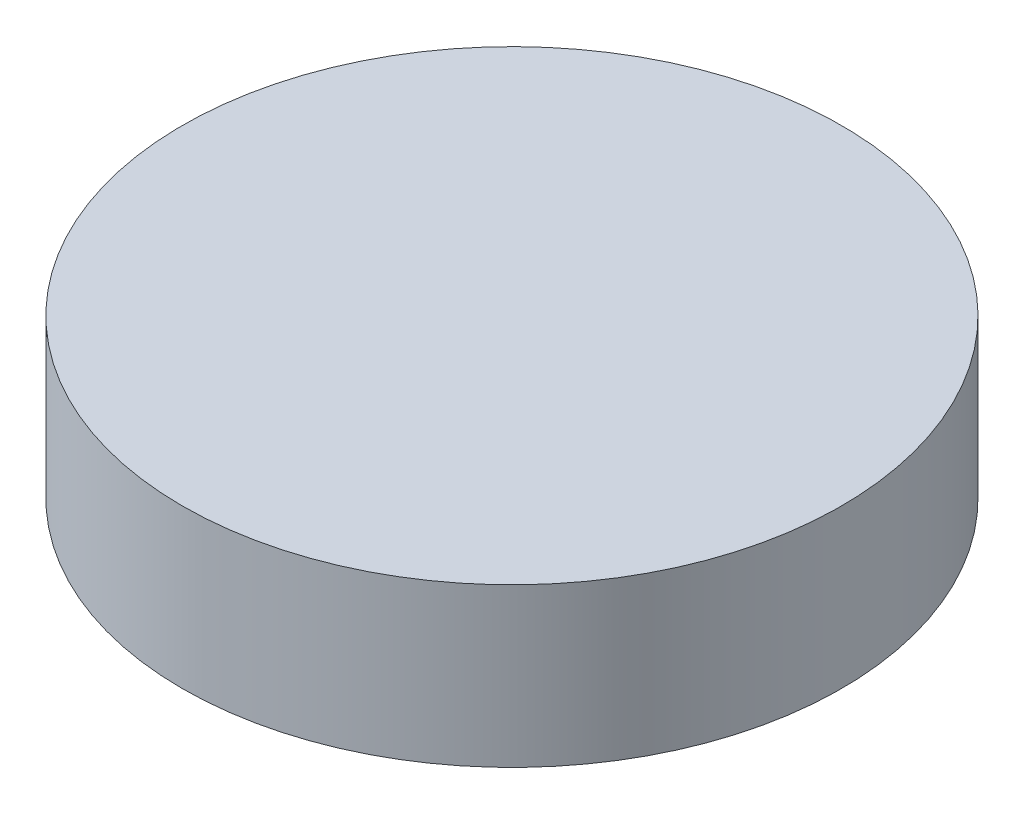
SolidWorks part; units mm, degrees
ref_plane "Front Plane" through (0, 0, 0) normal (0, 0, 1) x (1, 0, 0)
ref_plane "Top Plane" through (0, 0, 0) normal (0, 1, 0) x (1, 0, 0)
ref_plane "Right Plane" through (0, 0, 0) normal (1, 0, 0) x (0, 0, -1)
other "Configuration Table"
sketch "Sketch1" plane through (0, 0, 0) normal (0, 1, 0) x (1, 0, 0)
  circle A0 centre (50, 770) radius 25
extrude "OVEN_ayar_ayagi_3" add sketch "Sketch1" along normal blind 12 separate body
